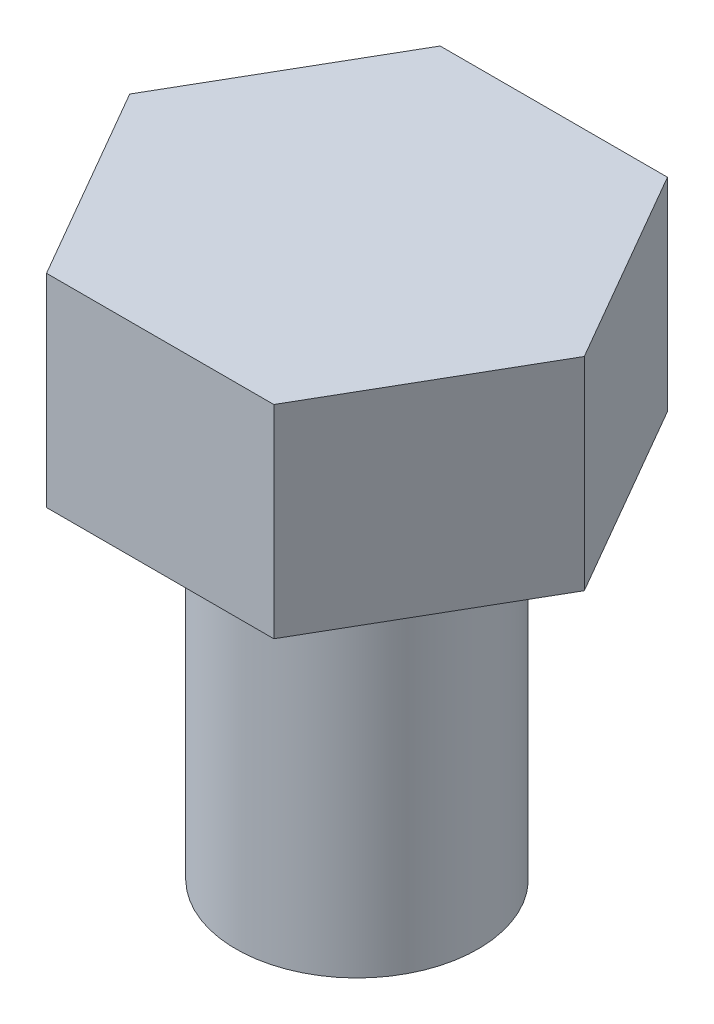
SolidWorks part; units mm, degrees
ref_plane "Front Plane" through (0, 0, 0) normal (0, 0, 1) x (1, 0, 0)
ref_plane "Top Plane" through (0, 0, 0) normal (0, 1, 0) x (1, 0, 0)
ref_plane "Right Plane" through (0, 0, 0) normal (1, 0, 0) x (0, 0, -1)
sketch "Sketch1" plane through (0, 0, 0) normal (0, 1, 0) x (1, 0, 0)
  line L1 (7.5056, 0) -> (3.7528, 6.5)
  line L2 (3.7528, 6.5) -> (-3.7528, 6.5)
  line L3 (-3.7528, 6.5) -> (-7.5056, 0)
  line L4 (-7.5056, 0) -> (-3.7528, -6.5)
  line L5 (-3.7528, -6.5) -> (3.7528, -6.5)
  line L6 (3.7528, -6.5) -> (7.5056, 0)
  circle A1 centre (0, 0) radius 6.5 construction
  dimension "D1" = 13
extrude "Boss-Extrude1" add sketch "Sketch1" along normal blind 6.7
sketch "Sketch2" plane through (0, 0, 0) normal (0, -1, 0) x (1, 0, 0)
  circle A0 centre (0, 0) radius 4
  dimension "D1" = 8
extrude "Boss-Extrude2" add sketch "Sketch2" along normal blind 12
